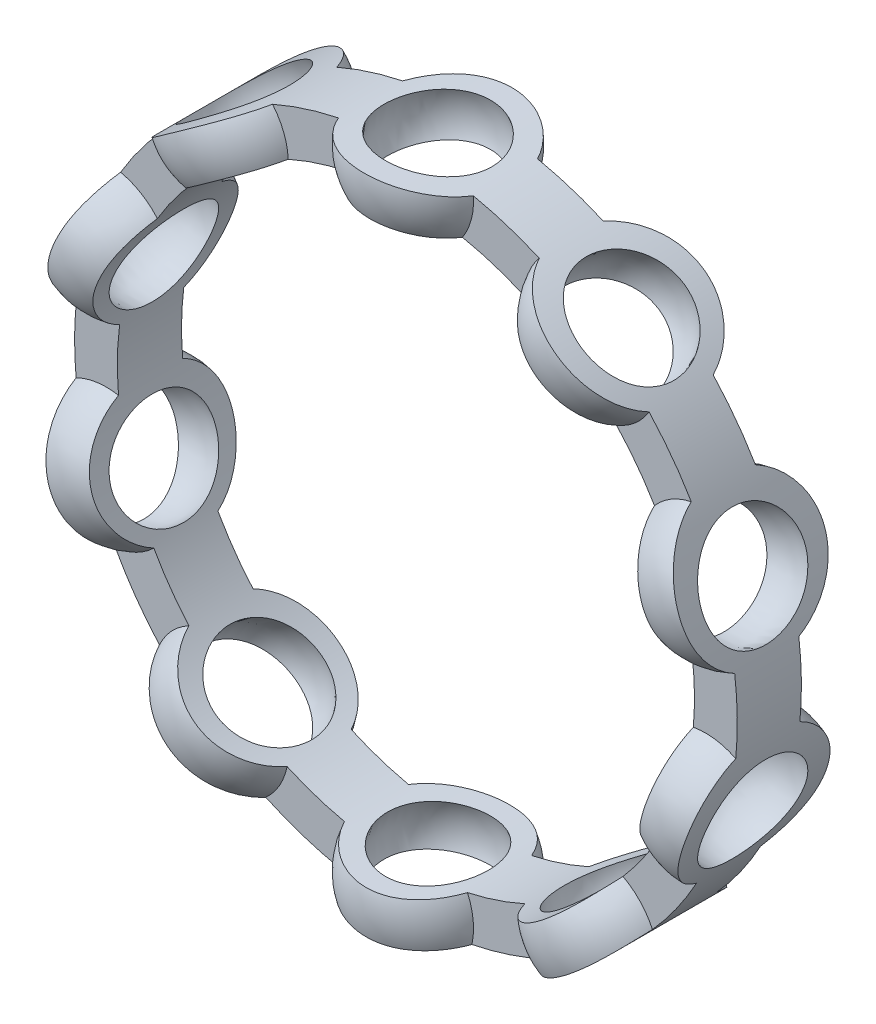
SolidWorks part; units mm, degrees
material "1.4000 (X6Cr13)"
ref_plane "前视基准面" through (0, 0, 0) normal (0, 0, 1) x (1, 0, 0)
ref_plane "上视基准面" through (0, 0, 0) normal (0, 1, 0) x (1, 0, 0)
ref_plane "右视基准面" through (0, 0, 0) normal (1, 0, 0) x (0, 0, -1)
sketch "草图1" plane through (0, 0, 0) normal (0, 0, 1) x (1, 0, 0)
  circle A0 centre (0, 0) radius 12.5
  dimension "D1" = 25
extrude "凸台-拉伸1" add sketch "草图1" along normal mid plane 1.5
sketch "草图2" plane through (0, 0, 0) normal (1, 0, 0) x (0, 0, -1)
  line L0 (-1.75, -7.25) -> (1.75, -7.25)
  arc A0 (-1.75, -7.25) -> (1.75, -7.25) centre (0, -7.25) ccw
  point P2 (0, -0.76)
  point P4 (0, -0.76)
  dimension "D3" = 3.5
  dimension "D1" = 0
  dimension "D2" = 7.25
revolve "旋转1" add sketch "草图2" angle 360 about L0
pattern_circular "阵列(圆周)1" count 10 over 360 about axis through (0, 0.1179, 0) along (0, 0, 1) of "旋转1"
sketch "草图3" plane through (0, 0, -0.75) normal (0, 0, -1) x (-1, 0, 0)
  circle A0 centre (0, 0) radius 6.75
  circle A1 centre (0, 0) radius 7.75
  dimension "D1" = 15.5
  dimension "D2" = 13.5
extrude "切除-拉伸1" cut sketch "草图3" against normal mid plane 10 flip side to cut
sketch "草图7" plane through (0, 0, 0) normal (1, 0, 0) x (0, 0, -1)
  line L0 (-1.325, -7.25) -> (1.325, -7.25)
  arc A0 (-1.325, -7.25) -> (1.325, -7.25) centre (0, -7.25) ccw
  dimension "D1" = 2.65
  dimension "D2" = 7.25
revolve "切除-旋转3" cut sketch "草图7" angle 360 about L0
pattern_circular "阵列(圆周)2" count 10 over 360 about axis through (0, 0, 0) along (0, 0, 1) of "切除-旋转3"
